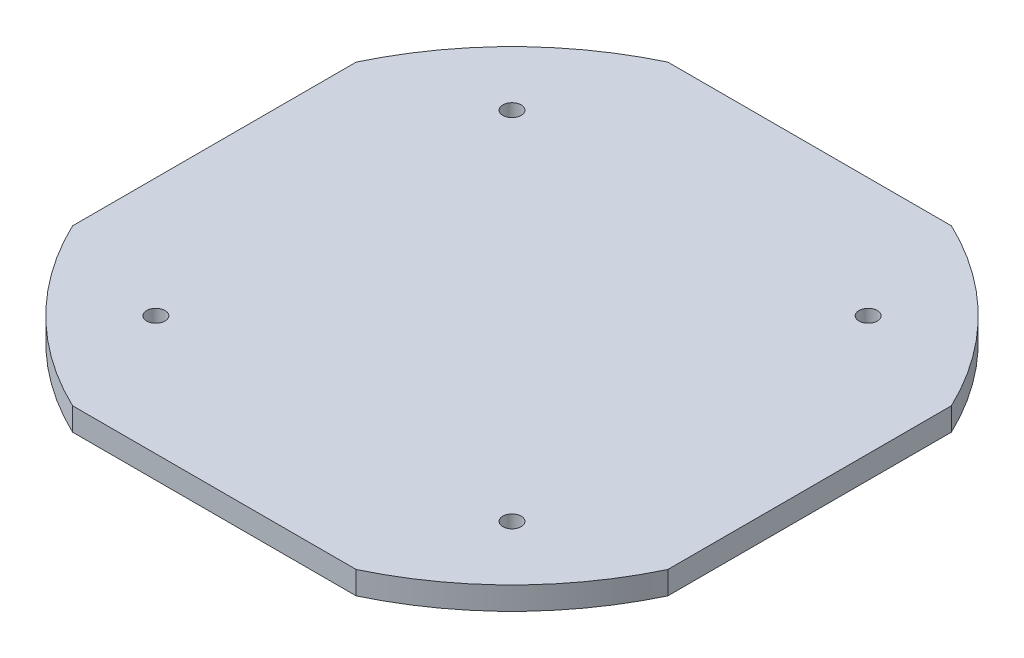
SolidWorks part; units mm, degrees
ref_plane "Front Plane" through (0, 0, 0) normal (0, 0, 1) x (1, 0, 0)
ref_plane "Top Plane" through (0, 0, 0) normal (0, 1, 0) x (1, 0, 0)
ref_plane "Right Plane" through (0, 0, 0) normal (1, 0, 0) x (0, 0, -1)
sketch "Sketch1" plane through (0, 0, 0) normal (0, 1, 0) x (1, 0, 0)
  line L0 (65, 30.9677) -> (65, -30.9677)
  line L1 (65, 30.9677) -> (0, 0) construction
  line L2 (0, 0) -> (65, -30.9677) construction
  line L3 (30.9677, -65) -> (0, 0) construction
  line L4 (0, 0) -> (-30.9677, -65) construction
  line L5 (30.9677, -65) -> (-30.9677, -65)
  line L6 (-65, -30.9677) -> (0, 0) construction
  line L7 (0, 0) -> (-65, 30.9677) construction
  line L8 (-65, -30.9677) -> (-65, 30.9677)
  line L9 (-30.9677, 65) -> (0, 0) construction
  line L10 (0, 0) -> (30.9677, 65) construction
  line L11 (-30.9677, 65) -> (30.9677, 65)
  arc A0 (-65, -30.9677) -> (-30.9677, -65) centre (0, 0) ccw
  arc A1 (-65, 30.9677) -> (-65, -30.9677) centre (0, 0) ccw construction
  arc A2 (30.9677, 65) -> (-30.9677, 65) centre (0, 0) ccw construction
  arc A3 (-30.9677, 65) -> (-65, 30.9677) centre (0, 0) ccw
  arc A4 (65, -30.9677) -> (65, 30.9677) centre (0, 0) ccw construction
  arc A5 (65, 30.9677) -> (30.9677, 65) centre (0, 0) ccw
  arc A6 (-30.9677, -65) -> (30.9677, -65) centre (0, 0) ccw construction
  arc A7 (30.9677, -65) -> (65, -30.9677) centre (0, 0) ccw
  point P14 (0, 0)
  dimension "D1" = 144
  dimension "D2" = 65
  dimension "D3" = 4
extrude "Boss-Extrude1" add sketch "Sketch1" along normal blind 5
sketch "Sketch2" plane through (0, 5, 0) normal (0, 1, 0) x (1, 0, 0)
  point P0 (37.7109, 0)
  point P2 (0, 39.9735)
  point P4 (-38.2765, 0)
  point P6 (0, -34.694)
sketch "Sketch5" plane through (0, 5, 0) normal (0, 1, 0) x (1, 0, 0)
  line L0 (38.8909, 38.8909) -> (0, 0) construction
  line L1 (0, 0) -> (-38.8909, -38.8909) construction
  line L3 (-38.8909, 38.8909) -> (0, 0) construction
  line L4 (0, 0) -> (38.8909, -38.8909) construction
  line L5 (0, 0) -> (0, 65) construction
  line L6 (30.9677, 65) -> (-30.9677, 65) construction
  point P0 (38.8909, 38.8909)
  point P3 (38.8909, -38.8909)
  point P5 (-38.8909, -38.8909)
  point P7 (-38.8909, 38.8909)
  dimension "D1" = 45
  dimension "D2" = 55
hole_wizard "Ø4.0mm Dowel Hole2" positions "Sketch5" profile "Sketch6" hole size "Ø4.0" standard "ISO" end condition through all
sketch "Sketch6" plane through (38.8909, 5, -38.8909) normal (1, 0, 0) x (0, 0, 1)
  line L0 (0, 0) -> (0, 5)
  line L1 (0, 5) -> (2, 5)
  line L2 (2, 5) -> (2, 0)
  line L5 (2, 0) -> (0, 0)
  line L11 (0, -6.35) -> (0, 107.95) construction
  dimension "Thru Hole Dia." = 4
  dimension "Thru Hole Depth" = 5
sketch "Sketch7" plane through (0, 0, 0) normal (0, -1, 0) x (1, 0, 0)
  line L0 (38.85, -20.1) -> (-38.85, -20.1) construction
  line L1 (-38.85, 20.1) -> (38.85, 20.1) construction
  circle A0 centre (27.8, -9.75) radius 1.7 construction
  circle A1 centre (27.8, 9.75) radius 1.7 construction
  circle A2 centre (-27.8, 9.75) radius 1.7 construction
  circle A3 centre (-27.8, -9.75) radius 1.7 construction
  point P12 (0, 0)
  point P13 (0, 0)
sketch "Sketch8" plane through (0, 5, 0) normal (0, 1, 0) x (1, 0, 0)
  circle A0 centre (0, 0) radius 10 construction
  point P3 (0, 0)
  dimension "D1" = 20
